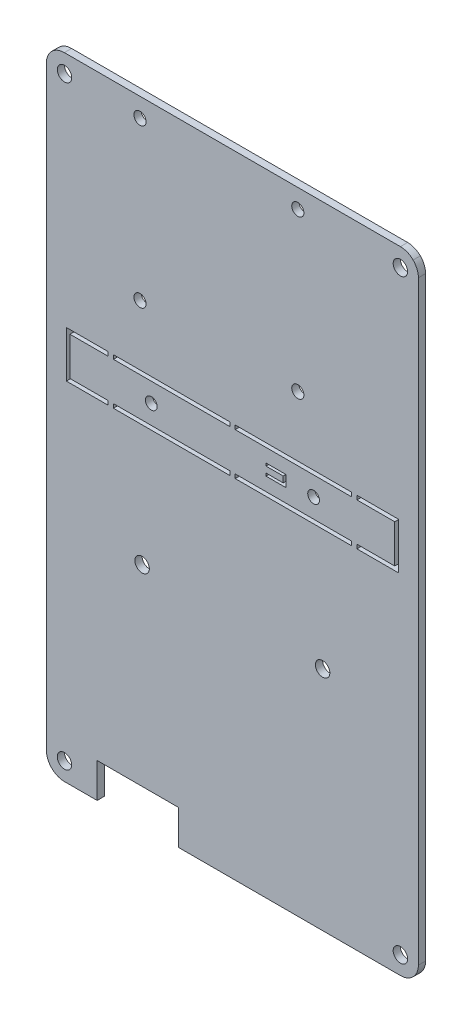
SolidWorks part; units mm, degrees
ref_plane "Front Plane" through (0, 0, 0) normal (0, 0, 1) x (1, 0, 0)
ref_plane "Top Plane" through (0, 0, 0) normal (0, 1, 0) x (1, 0, 0)
ref_plane "Right Plane" through (0, 0, 0) normal (1, 0, 0) x (0, 0, -1)
sketch "Model" plane through (0, 0, 0) normal (0, 0, 1) x (1, 0, 0)
  line L0 (70.0024, -162.3047) -> (88.0029, -162.3047)
  line L1 (72.4144, -82.5502) -> (63.1754, -82.5502)
  line L2 (72.4144, -83.4501) -> (63.9755, -83.4501)
  line L3 (72.4144, -91.9504) -> (72.4144, -92.8504)
  line L4 (73.6145, -82.5502) -> (73.6145, -83.4501)
  line L5 (126.4162, -82.5502) -> (126.4162, -83.4501)
  line L6 (73.6145, -91.9504) -> (73.6145, -92.8504)
  line L7 (126.4162, -91.9504) -> (126.4162, -92.8504)
  line L8 (127.6163, -91.9504) -> (127.6163, -92.8504)
  line L9 (127.6163, -82.5502) -> (127.6163, -83.4501)
  line L10 (136.0029, -91.9504) -> (136.0029, -83.4501)
  line L11 (136.8029, -82.5502) -> (136.8029, -92.8504)
  line L12 (73.6145, -83.4501) -> (99.4153, -83.4501)
  line L13 (88.0029, -162.3047) -> (88.0029, -169.9868)
  line L14 (141.2463, -33.9638) -> (141.2461, -165.9996)
  line L15 (107.4536, -86.4364) -> (111.8538, -86.4364)
  line L16 (107.4536, -88.3641) -> (111.2538, -88.3641)
  line L17 (70.0024, -169.9868) -> (62.7306, -169.9866)
  line L18 (100.6154, -82.5502) -> (100.6154, -83.4501)
  line L19 (100.6154, -91.9504) -> (100.6154, -92.8504)
  line L20 (100.6154, -91.9504) -> (126.4162, -91.9504)
  line L21 (99.4153, -91.9504) -> (99.4153, -92.8504)
  line L22 (63.1754, -82.5502) -> (63.1754, -92.8504)
  line L23 (72.4144, -82.5502) -> (72.4144, -83.4501)
  line L24 (73.6145, -92.8504) -> (99.4153, -92.8504)
  line L25 (111.8538, -86.4364) -> (111.8538, -88.9641)
  line L26 (107.4536, -88.3641) -> (107.4536, -88.9641)
  line L27 (106.1536, -88.9641) -> (106.7536, -88.9641) construction
  line L28 (107.4536, -87.0364) -> (111.2538, -87.0364)
  line L29 (106.7536, -86.4364) -> (106.7536, -88.9641) construction
  line L30 (107.4536, -86.4364) -> (107.4536, -87.0364)
  line L31 (63.9755, -83.4501) -> (63.9755, -91.9504)
  line L32 (127.6163, -83.4501) -> (136.0029, -83.4501)
  line L33 (127.6163, -82.5502) -> (136.8029, -82.5502)
  line L34 (63.9755, -91.9504) -> (72.4144, -91.9504)
  line L35 (70.0024, -169.9868) -> (70.0024, -162.3047)
  line L36 (106.1536, -86.4364) -> (106.1536, -88.9641) construction
  line L37 (100.6154, -82.5502) -> (126.4162, -82.5502)
  line L38 (137.2589, -29.9767) -> (62.7305, -29.9767)
  line L39 (88.0029, -169.9868) -> (137.2587, -169.9868)
  line L40 (127.6163, -91.9504) -> (136.0029, -91.9504)
  line L41 (111.2538, -87.0364) -> (111.2538, -88.3641)
  line L42 (107.4536, -88.9641) -> (111.8538, -88.9641)
  line L43 (73.6145, -82.5502) -> (99.4153, -82.5502)
  line L44 (106.1536, -86.4364) -> (106.7536, -86.4364) construction
  line L45 (73.6145, -91.9504) -> (99.4153, -91.9504)
  line L46 (100.6154, -83.4501) -> (126.4162, -83.4501)
  line L47 (63.1754, -92.8504) -> (72.4144, -92.8504)
  line L48 (127.6163, -92.8504) -> (136.8029, -92.8504)
  line L49 (100.6154, -92.8504) -> (126.4162, -92.8504)
  line L50 (99.4153, -82.5502) -> (99.4153, -83.4501)
  line L51 (58.7434, -33.964) -> (58.7432, -165.9996)
  line L52 (135.6894, -83.7631) -> (73.0025, -83.7631) construction
  line L53 (73.0025, -91.6374) -> (135.6894, -91.6374) construction
  line L54 (70.4607, -86.0492) -> (64.289, -86.0492) construction
  line L55 (70.7147, -86.0492) -> (135.6894, -86.0492) construction
  line L56 (64.289, -89.3513) -> (70.4607, -89.3513) construction
  line L57 (72.7467, -91.6374) -> (64.289, -91.6374) construction
  line L58 (135.6894, -89.3513) -> (70.7147, -89.3513) construction
  line L59 (64.289, -83.7631) -> (72.7467, -83.7631) construction
  line L60 (69.5023, -87.3002) -> (69.5023, -88.1003) construction
  line L61 (69.5023, -88.1003) -> (69.0023, -88.1003) construction
  line L62 (69.0023, -88.1003) -> (69.0023, -87.3002) construction
  line L63 (69.0023, -87.3002) -> (69.5023, -87.3002) construction
  line L64 (68.0023, -87.3002) -> (68.0023, -88.1003) construction
  line L65 (68.0023, -88.1003) -> (67.5023, -88.1003) construction
  line L66 (67.5023, -88.1003) -> (67.5023, -87.3002) construction
  line L67 (67.5023, -87.3002) -> (68.0023, -87.3002) construction
  line L68 (78.5026, -87.3002) -> (78.5026, -88.1003) construction
  line L69 (78.5026, -88.1003) -> (78.0026, -88.1003) construction
  line L70 (78.0026, -88.1003) -> (78.0026, -87.3002) construction
  line L71 (78.0026, -87.3002) -> (78.5026, -87.3002) construction
  line L72 (77.0026, -87.3002) -> (77.0026, -88.1003) construction
  line L73 (77.0026, -88.1003) -> (76.5026, -88.1003) construction
  line L74 (76.5026, -88.1003) -> (76.5026, -87.3002) construction
  line L75 (76.5026, -87.3002) -> (77.0026, -87.3002) construction
  line L76 (87.503, -87.3002) -> (87.503, -88.1003) construction
  line L77 (87.503, -88.1003) -> (87.0029, -88.1003) construction
  line L78 (87.0029, -88.1003) -> (87.0029, -87.3002) construction
  line L79 (87.0029, -87.3002) -> (87.503, -87.3002) construction
  line L80 (86.0029, -87.3002) -> (86.0029, -88.1003) construction
  line L81 (86.0029, -88.1003) -> (85.5029, -88.1003) construction
  line L82 (85.5029, -88.1003) -> (85.5029, -87.3002) construction
  line L83 (85.5029, -87.3002) -> (86.0029, -87.3002) construction
  line L84 (96.5033, -87.3002) -> (96.5033, -88.1003) construction
  line L85 (96.5033, -88.1003) -> (96.0032, -88.1003) construction
  line L86 (96.0032, -88.1003) -> (96.0032, -87.3002) construction
  line L87 (96.0032, -87.3002) -> (96.5033, -87.3002) construction
  line L88 (95.0032, -87.3002) -> (95.0032, -88.1003) construction
  line L89 (95.0032, -88.1003) -> (94.5032, -88.1003) construction
  line L90 (94.5032, -88.1003) -> (94.5032, -87.3002) construction
  line L91 (94.5032, -87.3002) -> (95.0032, -87.3002) construction
  line L92 (105.5036, -87.3002) -> (105.5036, -88.1003) construction
  line L93 (105.5036, -88.1003) -> (105.0035, -88.1003) construction
  line L94 (105.0035, -88.1003) -> (105.0035, -87.3002) construction
  line L95 (105.0035, -87.3002) -> (105.5036, -87.3002) construction
  line L96 (104.0035, -87.3002) -> (104.0035, -88.1003) construction
  line L97 (104.0035, -88.1003) -> (103.5035, -88.1003) construction
  line L98 (103.5035, -88.1003) -> (103.5035, -87.3002) construction
  line L99 (103.5035, -87.3002) -> (104.0035, -87.3002) construction
  line L100 (123.5042, -87.3002) -> (123.5042, -88.1003) construction
  line L101 (123.5042, -88.1003) -> (123.0042, -88.1003) construction
  line L102 (123.0042, -88.1003) -> (123.0042, -87.3002) construction
  line L103 (123.0042, -87.3002) -> (123.5042, -87.3002) construction
  line L104 (122.0041, -87.3002) -> (122.0041, -88.1003) construction
  line L105 (122.0041, -88.1003) -> (121.5041, -88.1003) construction
  line L106 (121.5041, -88.1003) -> (121.5041, -87.3002) construction
  line L107 (121.5041, -87.3002) -> (122.0041, -87.3002) construction
  line L108 (114.5039, -87.3002) -> (114.5039, -88.1003) construction
  line L109 (114.5039, -88.1003) -> (114.0038, -88.1003) construction
  line L110 (114.0038, -88.1003) -> (114.0038, -87.3002) construction
  line L111 (114.0038, -87.3002) -> (114.5039, -87.3002) construction
  line L112 (113.0038, -87.3002) -> (113.0038, -88.1003) construction
  line L113 (113.0038, -88.1003) -> (112.5038, -88.1003) construction
  line L114 (112.5038, -88.1003) -> (112.5038, -87.3002) construction
  line L115 (112.5038, -87.3002) -> (113.0038, -87.3002) construction
  line L116 (110.9637, -87.8702) -> (110.9531, -87.9238) construction
  line L117 (110.9531, -87.9238) -> (110.9227, -87.9692) construction
  line L118 (110.9227, -87.9692) -> (110.8773, -87.9996) construction
  line L119 (110.8773, -87.9996) -> (110.8237, -88.0102) construction
  line L120 (110.8237, -88.0102) -> (110.5437, -88.0102) construction
  line L121 (110.5437, -88.0102) -> (110.4901, -87.9996) construction
  line L122 (110.4901, -87.9996) -> (110.4447, -87.9692) construction
  line L123 (110.4447, -87.9692) -> (110.4144, -87.9238) construction
  line L124 (110.4144, -87.9238) -> (110.4037, -87.8702) construction
  line L125 (110.4037, -87.8702) -> (110.4037, -87.5302) construction
  line L126 (110.4037, -87.5302) -> (110.4144, -87.4767) construction
  line L127 (110.4144, -87.4767) -> (110.4447, -87.4312) construction
  line L128 (110.4447, -87.4312) -> (110.4901, -87.4009) construction
  line L129 (110.4901, -87.4009) -> (110.5437, -87.3902) construction
  line L130 (110.5437, -87.3902) -> (110.8237, -87.3902) construction
  line L131 (110.8237, -87.3902) -> (110.8773, -87.4009) construction
  line L132 (110.8773, -87.4009) -> (110.9227, -87.4312) construction
  line L133 (110.9227, -87.4312) -> (110.9531, -87.4767) construction
  line L134 (110.9531, -87.4767) -> (110.9637, -87.5302) construction
  line L135 (110.9637, -87.5302) -> (110.9637, -87.8702) construction
  line L136 (110.0037, -87.8702) -> (109.9931, -87.9238) construction
  line L137 (109.9931, -87.9238) -> (109.9627, -87.9692) construction
  line L138 (109.9627, -87.9692) -> (109.9173, -87.9996) construction
  line L139 (109.9173, -87.9996) -> (109.8637, -88.0102) construction
  line L140 (109.8637, -88.0102) -> (109.5837, -88.0102) construction
  line L141 (109.5837, -88.0102) -> (109.5301, -87.9996) construction
  line L142 (109.5301, -87.9996) -> (109.4847, -87.9692) construction
  line L143 (109.4847, -87.9692) -> (109.4544, -87.9238) construction
  line L144 (109.4544, -87.9238) -> (109.4437, -87.8702) construction
  line L145 (109.4437, -87.8702) -> (109.4437, -87.5302) construction
  line L146 (109.4437, -87.5302) -> (109.4544, -87.4767) construction
  line L147 (109.4544, -87.4767) -> (109.4847, -87.4312) construction
  line L148 (109.4847, -87.4312) -> (109.5301, -87.4009) construction
  line L149 (109.5301, -87.4009) -> (109.5837, -87.3902) construction
  line L150 (109.5837, -87.3902) -> (109.8637, -87.3902) construction
  line L151 (109.8637, -87.3902) -> (109.9173, -87.4009) construction
  line L152 (109.9173, -87.4009) -> (109.9627, -87.4312) construction
  line L153 (109.9627, -87.4312) -> (109.9931, -87.4767) construction
  line L154 (109.9931, -87.4767) -> (110.0037, -87.5302) construction
  line L155 (110.0037, -87.5302) -> (110.0037, -87.8702) construction
  line L156 (132.5045, -87.3002) -> (132.5045, -88.1003) construction
  line L157 (132.5045, -88.1003) -> (132.0045, -88.1003) construction
  line L158 (132.0045, -88.1003) -> (132.0045, -87.3002) construction
  line L159 (132.0045, -87.3002) -> (132.5045, -87.3002) construction
  line L160 (131.0044, -87.3002) -> (131.0044, -88.1003) construction
  line L161 (131.0044, -88.1003) -> (130.5044, -88.1003) construction
  line L162 (130.5044, -88.1003) -> (130.5044, -87.3002) construction
  line L163 (130.5044, -87.3002) -> (131.0044, -87.3002) construction
  line L164 (129.463, -38.0569) -> (129.4631, -31.1764) construction
  line L165 (121.4884, -38.057) -> (121.4884, -31.1764) construction
  line L166 (140.0614, -33.9896) -> (140.0614, -166.0159) construction
  line L167 (137.2606, -168.8164) -> (62.7465, -168.8164) construction
  line L168 (137.2606, -31.1891) -> (62.7465, -31.1891) construction
  line L169 (59.9457, -33.9896) -> (59.9457, -166.0159) construction
  line L170 (138.0026, -151.9543) -> (139.0027, -151.9543) construction
  line L171 (139.0027, -151.9543) -> (139.0027, -152.8544) construction
  line L172 (139.0027, -152.8544) -> (138.0026, -152.8544) construction
  line L173 (138.0026, -152.8544) -> (138.0026, -151.9543) construction
  line L174 (138.0026, -156.0545) -> (139.0027, -156.0545) construction
  line L175 (139.0027, -156.0545) -> (139.0027, -156.9545) construction
  line L176 (139.0027, -156.9545) -> (138.0026, -156.9545) construction
  line L177 (138.0026, -156.9545) -> (138.0026, -156.0545) construction
  line L178 (136.4026, -156.0545) -> (137.4026, -156.0545) construction
  line L179 (137.4026, -156.0545) -> (137.4026, -156.9545) construction
  line L180 (137.4026, -156.9545) -> (136.4026, -156.9545) construction
  line L181 (136.4026, -156.9545) -> (136.4026, -156.0545) construction
  line L182 (136.4026, -151.9543) -> (137.4026, -151.9543) construction
  line L183 (137.4026, -151.9543) -> (137.4026, -152.8544) construction
  line L184 (137.4026, -152.8544) -> (136.4026, -152.8544) construction
  line L185 (136.4026, -152.8544) -> (136.4026, -151.9543) construction
  line L186 (74.8825, -163.3947) -> (74.8825, -123.0934) construction
  line L187 (129.2444, -123.0934) -> (74.8825, -123.0934) construction
  line L188 (129.2444, -163.3947) -> (74.8825, -163.3947) construction
  line L189 (129.2444, -123.0934) -> (129.2444, -163.3947) construction
  line L190 (131.5044, -124.5034) -> (131.5044, -162.0047) construction
  line L191 (77.1826, -160.5046) -> (77.1826, -126.0035) construction
  line L192 (122.8241, -126.0035) -> (122.8241, -160.5046) construction
  line L193 (122.8241, -126.0035) -> (77.1826, -126.0035) construction
  line L194 (129.5044, -124.5034) -> (129.5044, -162.0047) construction
  line L195 (122.8241, -160.4846) -> (77.1826, -160.4846) construction
  line L196 (107.0536, -155.0434) -> (107.0536, -153.7434) construction
  line L197 (107.0536, -153.7434) -> (109.0537, -153.7434) construction
  line L198 (109.0537, -153.7434) -> (109.0537, -155.0434) construction
  line L199 (109.0537, -155.0434) -> (107.0536, -155.0434) construction
  line L200 (90.9531, -155.0434) -> (90.9531, -153.7434) construction
  line L201 (90.9531, -153.7434) -> (92.9531, -153.7434) construction
  line L202 (92.9531, -153.7434) -> (92.9531, -155.0434) construction
  line L203 (92.9531, -155.0434) -> (90.9531, -155.0434) construction
  line L204 (105.6036, -152.1933) -> (105.6036, -151.1933) construction
  line L205 (105.6036, -151.1933) -> (105.9036, -151.1933) construction
  line L206 (105.9036, -151.1933) -> (105.9036, -152.1933) construction
  line L207 (105.9036, -152.1933) -> (105.6036, -152.1933) construction
  line L208 (105.1035, -152.1933) -> (105.1035, -151.1933) construction
  line L209 (105.1035, -151.1933) -> (105.4036, -151.1933) construction
  line L210 (105.4036, -151.1933) -> (105.4036, -152.1933) construction
  line L211 (105.4036, -152.1933) -> (105.1035, -152.1933) construction
  line L212 (104.6035, -152.1933) -> (104.6035, -151.1933) construction
  line L213 (104.6035, -151.1933) -> (104.9035, -151.1933) construction
  line L214 (104.9035, -151.1933) -> (104.9035, -152.1933) construction
  line L215 (104.9035, -152.1933) -> (104.6035, -152.1933) construction
  line L216 (104.1035, -152.1933) -> (104.1035, -151.1933) construction
  line L217 (104.1035, -151.1933) -> (104.4035, -151.1933) construction
  line L218 (104.4035, -151.1933) -> (104.4035, -152.1933) construction
  line L219 (104.4035, -152.1933) -> (104.1035, -152.1933) construction
  line L220 (103.6035, -152.1933) -> (103.6035, -151.1933) construction
  line L221 (103.6035, -151.1933) -> (103.9035, -151.1933) construction
  line L222 (103.9035, -151.1933) -> (103.9035, -152.1933) construction
  line L223 (103.9035, -152.1933) -> (103.6035, -152.1933) construction
  line L224 (103.1035, -152.1933) -> (103.1035, -151.1933) construction
  line L225 (103.1035, -151.1933) -> (103.4035, -151.1933) construction
  line L226 (103.4035, -151.1933) -> (103.4035, -152.1933) construction
  line L227 (103.4035, -152.1933) -> (103.1035, -152.1933) construction
  line L228 (102.6035, -152.1933) -> (102.6035, -151.1933) construction
  line L229 (102.6035, -151.1933) -> (102.9035, -151.1933) construction
  line L230 (102.9035, -151.1933) -> (102.9035, -152.1933) construction
  line L231 (102.9035, -152.1933) -> (102.6035, -152.1933) construction
  line L232 (102.1034, -152.1933) -> (102.1034, -151.1933) construction
  line L233 (102.1034, -151.1933) -> (102.4035, -151.1933) construction
  line L234 (102.4035, -151.1933) -> (102.4035, -152.1933) construction
  line L235 (102.4035, -152.1933) -> (102.1034, -152.1933) construction
  line L236 (101.6034, -152.1933) -> (101.6034, -151.1933) construction
  line L237 (101.6034, -151.1933) -> (101.9034, -151.1933) construction
  line L238 (101.9034, -151.1933) -> (101.9034, -152.1933) construction
  line L239 (101.9034, -152.1933) -> (101.6034, -152.1933) construction
  line L240 (101.1034, -152.1933) -> (101.1034, -151.1933) construction
  line L241 (101.1034, -151.1933) -> (101.4034, -151.1933) construction
  line L242 (101.4034, -151.1933) -> (101.4034, -152.1933) construction
  line L243 (101.4034, -152.1933) -> (101.1034, -152.1933) construction
  line L244 (100.6034, -152.1933) -> (100.6034, -151.1933) construction
  line L245 (100.6034, -151.1933) -> (100.9034, -151.1933) construction
  line L246 (100.9034, -151.1933) -> (100.9034, -152.1933) construction
  line L247 (100.9034, -152.1933) -> (100.6034, -152.1933) construction
  line L248 (100.1034, -152.1933) -> (100.1034, -151.1933) construction
  line L249 (100.1034, -151.1933) -> (100.4034, -151.1933) construction
  line L250 (100.4034, -151.1933) -> (100.4034, -152.1933) construction
  line L251 (100.4034, -152.1933) -> (100.1034, -152.1933) construction
  line L252 (99.6034, -152.1933) -> (99.6034, -151.1933) construction
  line L253 (99.6034, -151.1933) -> (99.9034, -151.1933) construction
  line L254 (99.9034, -151.1933) -> (99.9034, -152.1933) construction
  line L255 (99.9034, -152.1933) -> (99.6034, -152.1933) construction
  line L256 (99.1033, -152.1933) -> (99.1033, -151.1933) construction
  line L257 (99.1033, -151.1933) -> (99.4034, -151.1933) construction
  line L258 (99.4034, -151.1933) -> (99.4034, -152.1933) construction
  line L259 (99.4034, -152.1933) -> (99.1033, -152.1933) construction
  line L260 (98.6033, -152.1933) -> (98.6033, -151.1933) construction
  line L261 (98.6033, -151.1933) -> (98.9033, -151.1933) construction
  line L262 (98.9033, -151.1933) -> (98.9033, -152.1933) construction
  line L263 (98.9033, -152.1933) -> (98.6033, -152.1933) construction
  line L264 (98.1033, -152.1933) -> (98.1033, -151.1933) construction
  line L265 (98.1033, -151.1933) -> (98.4033, -151.1933) construction
  line L266 (98.4033, -151.1933) -> (98.4033, -152.1933) construction
  line L267 (98.4033, -152.1933) -> (98.1033, -152.1933) construction
  line L268 (97.6033, -152.1933) -> (97.6033, -151.1933) construction
  line L269 (97.6033, -151.1933) -> (97.9033, -151.1933) construction
  line L270 (97.9033, -151.1933) -> (97.9033, -152.1933) construction
  line L271 (97.9033, -152.1933) -> (97.6033, -152.1933) construction
  line L272 (97.1033, -152.1933) -> (97.1033, -151.1933) construction
  line L273 (97.1033, -151.1933) -> (97.4033, -151.1933) construction
  line L274 (97.4033, -151.1933) -> (97.4033, -152.1933) construction
  line L275 (97.4033, -152.1933) -> (97.1033, -152.1933) construction
  line L276 (96.6033, -152.1933) -> (96.6033, -151.1933) construction
  line L277 (96.6033, -151.1933) -> (96.9033, -151.1933) construction
  line L278 (96.9033, -151.1933) -> (96.9033, -152.1933) construction
  line L279 (96.9033, -152.1933) -> (96.6033, -152.1933) construction
  line L280 (96.1032, -152.1933) -> (96.1032, -151.1933) construction
  line L281 (96.1032, -151.1933) -> (96.4033, -151.1933) construction
  line L282 (96.4033, -151.1933) -> (96.4033, -152.1933) construction
  line L283 (96.4033, -152.1933) -> (96.1032, -152.1933) construction
  line L284 (95.6032, -152.1933) -> (95.6032, -151.1933) construction
  line L285 (95.6032, -151.1933) -> (95.9032, -151.1933) construction
  line L286 (95.9032, -151.1933) -> (95.9032, -152.1933) construction
  line L287 (95.9032, -152.1933) -> (95.6032, -152.1933) construction
  line L288 (95.1032, -152.1933) -> (95.1032, -151.1933) construction
  line L289 (95.1032, -151.1933) -> (95.4032, -151.1933) construction
  line L290 (95.4032, -151.1933) -> (95.4032, -152.1933) construction
  line L291 (95.4032, -152.1933) -> (95.1032, -152.1933) construction
  line L292 (94.6032, -152.1933) -> (94.6032, -151.1933) construction
  line L293 (94.6032, -151.1933) -> (94.9032, -151.1933) construction
  line L294 (94.9032, -151.1933) -> (94.9032, -152.1933) construction
  line L295 (94.9032, -152.1933) -> (94.6032, -152.1933) construction
  line L296 (94.1032, -152.1933) -> (94.1032, -151.1933) construction
  line L297 (94.1032, -151.1933) -> (94.4032, -151.1933) construction
  line L298 (94.4032, -151.1933) -> (94.4032, -152.1933) construction
  line L299 (94.4032, -152.1933) -> (94.1032, -152.1933) construction
  line L300 (137.0864, -46.2988) -> (137.0027, -46.2821) construction
  line L301 (137.0027, -46.2821) -> (136.9317, -46.2347) construction
  line L302 (136.9317, -46.2347) -> (136.8843, -46.1637) construction
  line L303 (136.8843, -46.1637) -> (136.8676, -46.08) construction
  line L304 (136.8676, -46.08) -> (136.8676, -45.6425) construction
  line L305 (136.8676, -45.6425) -> (136.8843, -45.5588) construction
  line L306 (136.8843, -45.5588) -> (136.9317, -45.4878) construction
  line L307 (136.9317, -45.4878) -> (137.0027, -45.4404) construction
  line L308 (137.0027, -45.4404) -> (137.0864, -45.4237) construction
  line L309 (137.0864, -45.4237) -> (137.5989, -45.4237) construction
  line L310 (137.5989, -45.4237) -> (137.6826, -45.4404) construction
  line L311 (137.6826, -45.4404) -> (137.7536, -45.4878) construction
  line L312 (137.7536, -45.4878) -> (137.801, -45.5588) construction
  line L313 (137.801, -45.5588) -> (137.8177, -45.6425) construction
  line L314 (137.8177, -45.6425) -> (137.8177, -46.08) construction
  line L315 (137.8177, -46.08) -> (137.801, -46.1637) construction
  line L316 (137.801, -46.1637) -> (137.7536, -46.2347) construction
  line L317 (137.7536, -46.2347) -> (137.6826, -46.2821) construction
  line L318 (137.6826, -46.2821) -> (137.5989, -46.2988) construction
  line L319 (137.5989, -46.2988) -> (137.0864, -46.2988) construction
  line L320 (137.0864, -44.7237) -> (137.0027, -44.7071) construction
  line L321 (137.0027, -44.7071) -> (136.9317, -44.6596) construction
  line L322 (136.9317, -44.6596) -> (136.8843, -44.5887) construction
  line L323 (136.8843, -44.5887) -> (136.8676, -44.505) construction
  line L324 (136.8676, -44.505) -> (136.8676, -44.0674) construction
  line L325 (136.8676, -44.0674) -> (136.8843, -43.9837) construction
  line L326 (136.8843, -43.9837) -> (136.9317, -43.9128) construction
  line L327 (136.9317, -43.9128) -> (137.0027, -43.8653) construction
  line L328 (137.0027, -43.8653) -> (137.0864, -43.8487) construction
  line L329 (137.0864, -43.8487) -> (137.5989, -43.8487) construction
  line L330 (137.5989, -43.8487) -> (137.6826, -43.8653) construction
  line L331 (137.6826, -43.8653) -> (137.7536, -43.9128) construction
  line L332 (137.7536, -43.9128) -> (137.801, -43.9837) construction
  line L333 (137.801, -43.9837) -> (137.8177, -44.0674) construction
  line L334 (137.8177, -44.0674) -> (137.8177, -44.505) construction
  line L335 (137.8177, -44.505) -> (137.801, -44.5887) construction
  line L336 (137.801, -44.5887) -> (137.7536, -44.6596) construction
  line L337 (137.7536, -44.6596) -> (137.6826, -44.7071) construction
  line L338 (137.6826, -44.7071) -> (137.5989, -44.7237) construction
  line L339 (137.5989, -44.7237) -> (137.0864, -44.7237) construction
  line L340 (127.8663, -61.6353) -> (124.4662, -61.6353) construction
  line L341 (124.4662, -61.6353) -> (124.4662, -60.1352) construction
  line L342 (124.4662, -60.1352) -> (127.8663, -60.1352) construction
  line L343 (127.8663, -60.1352) -> (127.8663, -61.6353) construction
  line L344 (127.8663, -68.3355) -> (124.4662, -68.3355) construction
  line L345 (124.4662, -68.3355) -> (124.4662, -66.8355) construction
  line L346 (124.4662, -66.8355) -> (127.8663, -66.8355) construction
  line L347 (127.8663, -66.8355) -> (127.8663, -68.3355) construction
  line L348 (122.3661, -65.7354) -> (118.866, -65.7354) construction
  line L349 (118.866, -65.7354) -> (118.866, -64.7354) construction
  line L350 (118.866, -64.7354) -> (122.3661, -64.7354) construction
  line L351 (122.3661, -64.7354) -> (122.3661, -65.7354) construction
  line L352 (122.3661, -63.7354) -> (118.866, -63.7354) construction
  line L353 (118.866, -63.7354) -> (118.866, -62.7353) construction
  line L354 (118.866, -62.7353) -> (122.3661, -62.7353) construction
  line L355 (122.3661, -62.7353) -> (122.3661, -63.7354) construction
  line L356 (106.5049, -141.111) -> (103.5042, -141.111) construction
  line L357 (103.5042, -141.111) -> (96.503, -141.111) construction
  line L358 (138.3113, -94.4016) -> (134.4739, -94.4016) construction
  line L359 (93.5022, -141.111) -> (93.5022, -134.3455) construction
  line L360 (95.5025, -139.1104) -> (96.5026, -139.1104) construction
  line L361 (61.6958, -93.2013) -> (66.158, -93.2013) construction
  line L362 (66.158, -93.2013) -> (95.5025, -135.1096) construction
  line L363 (103.5042, -139.1104) -> (96.5026, -139.1104) construction
  line L364 (106.5049, -134.3455) -> (106.5049, -141.111) construction
  line L365 (103.5042, -139.1104) -> (104.5043, -139.1104) construction
  line L366 (104.5043, -135.1096) -> (133.8491, -93.2013) construction
  line L367 (80.461, -115.7206) -> (65.5332, -94.4016) construction
  line L368 (133.8491, -93.2013) -> (138.311, -93.2013) construction
  line L369 (95.5025, -135.1096) -> (95.5025, -139.1104) construction
  line L370 (134.4739, -94.4016) -> (119.5463, -115.7204) construction
  line L371 (104.5043, -139.1104) -> (104.5043, -135.1096) construction
  line L372 (65.5038, -94.3713) -> (61.6929, -94.3715) construction
  line L373 (96.503, -141.111) -> (93.5022, -141.111) construction
  line L374 (99.9947, -29.9767) -> (99.9947, -73.0923) construction
  line L375 (110.0037, -87.7002) -> (110.4037, -87.7002) construction
  line L376 (110.2037, -87.7002) -> (110.2037, -87.3002) construction
  circle A0 centre (118.004, -87.7002) radius 1.3
  circle A1 centre (82.0028, -87.7002) radius 1.3
  circle A2 centre (114.5039, -69.1936) radius 1.35
  circle A3 centre (79.5027, -69.1936) radius 1.35
  circle A4 centre (79.5027, -34.1925) radius 1.35
  circle A5 centre (114.5039, -34.1925) radius 1.35
  circle A6 centre (62.7521, -34.0004) radius 1.6
  circle A7 centre (137.2546, -34.0004) radius 1.6
  circle A8 centre (137.2546, -166.0048) radius 1.6
  circle A9 centre (62.7521, -166.0048) radius 1.6
  circle A10 centre (79.9704, -119.7065) radius 1.6
  circle A11 centre (120.0076, -119.7065) radius 1.6
  circle A12 centre (77.5027, -87.7002) radius 1.35 construction
  spline S0 degree 3 poles (62.7521, -32.4003) (62.105, -32.4003) (61.5215, -32.7901) (61.2739, -33.388) knots 0 0 0 0 1 1 1 1 construction
  spline S1 degree 3 poles (61.2739, -33.388) (61.0262, -33.9859) (61.1631, -34.6742) (61.6207, -35.1318) knots 0 0 0 0 1 1 1 1 construction
  spline S2 degree 3 poles (61.6207, -35.1318) (62.0783, -35.5894) (62.7665, -35.7263) (63.3644, -35.4786) knots 0 0 0 0 1 1 1 1 construction
  spline S3 degree 3 poles (63.3644, -35.4786) (63.9623, -35.231) (64.3522, -34.6475) (64.3522, -34.0004) knots 0 0 0 0 1 1 1 1 construction
  spline S4 degree 3 poles (64.3522, -34.0004) (64.3522, -33.576) (64.1836, -33.169) (63.8835, -32.8689) knots 0 0 0 0 1 1 1 1 construction
  spline S5 degree 3 poles (63.8835, -32.8689) (63.5835, -32.5689) (63.1765, -32.4003) (62.7521, -32.4003) knots 0 0 0 0 1 1 1 1 construction
  spline S6 degree 3 poles (137.2546, -32.4003) (136.6075, -32.4003) (136.024, -32.7901) (135.7764, -33.388) knots 0 0 0 0 1 1 1 1 construction
  spline S7 degree 3 poles (135.7764, -33.388) (135.5287, -33.9859) (135.6656, -34.6742) (136.1232, -35.1318) knots 0 0 0 0 1 1 1 1 construction
  spline S8 degree 3 poles (136.1232, -35.1318) (136.5808, -35.5894) (137.269, -35.7263) (137.8669, -35.4786) knots 0 0 0 0 1 1 1 1 construction
  spline S9 degree 3 poles (137.8669, -35.4786) (138.4648, -35.231) (138.8547, -34.6475) (138.8547, -34.0004) knots 0 0 0 0 1 1 1 1 construction
  spline S10 degree 3 poles (138.8547, -34.0004) (138.8547, -33.576) (138.6861, -33.169) (138.386, -32.8689) knots 0 0 0 0 1 1 1 1 construction
  spline S11 degree 3 poles (138.386, -32.8689) (138.086, -32.5689) (137.679, -32.4003) (137.2546, -32.4003) knots 0 0 0 0 1 1 1 1 construction
  spline S12 degree 3 poles (62.7521, -164.4048) (62.105, -164.4048) (61.5215, -164.7946) (61.2739, -165.3925) knots 0 0 0 0 1 1 1 1 construction
  spline S13 degree 3 poles (61.2739, -165.3925) (61.0262, -165.9904) (61.1631, -166.6786) (61.6207, -167.1362) knots 0 0 0 0 1 1 1 1 construction
  spline S14 degree 3 poles (61.6207, -167.1362) (62.0783, -167.5938) (62.7665, -167.7307) (63.3644, -167.4831) knots 0 0 0 0 1 1 1 1 construction
  spline S15 degree 3 poles (63.3644, -167.4831) (63.9623, -167.2354) (64.3522, -166.652) (64.3522, -166.0048) knots 0 0 0 0 1 1 1 1 construction
  spline S16 degree 3 poles (64.3522, -166.0048) (64.3522, -165.5805) (64.1836, -165.1735) (63.8835, -164.8734) knots 0 0 0 0 1 1 1 1 construction
  spline S17 degree 3 poles (63.8835, -164.8734) (63.5835, -164.5733) (63.1765, -164.4048) (62.7521, -164.4048) knots 0 0 0 0 1 1 1 1 construction
  spline S18 degree 3 poles (137.2546, -164.4048) (136.6075, -164.4048) (136.024, -164.7946) (135.7764, -165.3925) knots 0 0 0 0 1 1 1 1 construction
  spline S19 degree 3 poles (135.7764, -165.3925) (135.5287, -165.9904) (135.6656, -166.6786) (136.1232, -167.1362) knots 0 0 0 0 1 1 1 1 construction
  spline S20 degree 3 poles (136.1232, -167.1362) (136.5808, -167.5938) (137.269, -167.7307) (137.8669, -167.4831) knots 0 0 0 0 1 1 1 1 construction
  spline S21 degree 3 poles (137.8669, -167.4831) (138.4648, -167.2354) (138.8547, -166.652) (138.8547, -166.0048) knots 0 0 0 0 1 1 1 1 construction
  spline S22 degree 3 poles (138.8547, -166.0048) (138.8547, -165.5805) (138.6861, -165.1735) (138.386, -164.8734) knots 0 0 0 0 1 1 1 1 construction
  spline S23 degree 3 poles (138.386, -164.8734) (138.086, -164.5733) (137.679, -164.4048) (137.2546, -164.4048) knots 0 0 0 0 1 1 1 1 construction
  spline S24 degree 3 poles (79.9704, -118.1065) (79.3232, -118.1065) (78.7398, -118.4964) (78.4921, -119.0943) knots 0 0 0 0 1 1 1 1 construction
  spline S25 degree 3 poles (78.4921, -119.0943) (78.2445, -119.6922) (78.3813, -120.3804) (78.839, -120.838) knots 0 0 0 0 1 1 1 1 construction
  spline S26 degree 3 poles (78.839, -120.838) (79.2966, -121.2956) (79.9848, -121.4325) (80.5827, -121.1849) knots 0 0 0 0 1 1 1 1 construction
  spline S27 degree 3 poles (80.5827, -121.1849) (81.1806, -120.9372) (81.5704, -120.3538) (81.5704, -119.7066) knots 0 0 0 0 1 1 1 1 construction
  spline S28 degree 3 poles (81.5704, -119.7066) (81.5704, -118.8229) (80.8541, -118.1065) (79.9704, -118.1065) knots 0 0 0 0 1 1 1 1 construction
  spline S29 degree 3 poles (120.0076, -118.1065) (119.3605, -118.1065) (118.777, -118.4964) (118.5294, -119.0943) knots 0 0 0 0 1 1 1 1 construction
  spline S30 degree 3 poles (118.5294, -119.0943) (118.2817, -119.6922) (118.4186, -120.3804) (118.8762, -120.838) knots 0 0 0 0 1 1 1 1 construction
  spline S31 degree 3 poles (118.8762, -120.838) (119.3338, -121.2956) (120.022, -121.4325) (120.6199, -121.1849) knots 0 0 0 0 1 1 1 1 construction
  spline S32 degree 3 poles (120.6199, -121.1849) (121.2178, -120.9372) (121.6077, -120.3538) (121.6077, -119.7066) knots 0 0 0 0 1 1 1 1 construction
  spline S33 degree 3 poles (121.6077, -119.7066) (121.6077, -119.2822) (121.4391, -118.8753) (121.139, -118.5752) knots 0 0 0 0 1 1 1 1 construction
  spline S34 degree 3 poles (121.139, -118.5752) (120.839, -118.2751) (120.432, -118.1065) (120.0076, -118.1065) knots 0 0 0 0 1 1 1 1 construction
  spline S35 degree 3 poles (118.004, -86.4002) (117.4782, -86.4002) (117.0041, -86.7169) (116.8029, -87.2027) knots 0 0 0 0 1 1 1 1 construction
  spline S36 degree 3 poles (116.8029, -87.2027) (116.6017, -87.6885) (116.7129, -88.2477) (117.0847, -88.6195) knots 0 0 0 0 1 1 1 1 construction
  spline S37 degree 3 poles (117.0847, -88.6195) (117.4565, -88.9913) (118.0157, -89.1025) (118.5015, -88.9013) knots 0 0 0 0 1 1 1 1 construction
  spline S38 degree 3 poles (118.5015, -88.9013) (118.9873, -88.7001) (119.304, -88.2261) (119.304, -87.7002) knots 0 0 0 0 1 1 1 1 construction
  spline S39 degree 3 poles (119.304, -87.7002) (119.304, -87.3554) (119.1671, -87.0248) (118.9233, -86.781) knots 0 0 0 0 1 1 1 1 construction
  spline S40 degree 3 poles (118.9233, -86.781) (118.6794, -86.5372) (118.3488, -86.4002) (118.004, -86.4002) knots 0 0 0 0 1 1 1 1 construction
  spline S41 degree 3 poles (82.0028, -86.4002) (81.4769, -86.4002) (81.0029, -86.7169) (80.8017, -87.2027) knots 0 0 0 0 1 1 1 1 construction
  spline S42 degree 3 poles (80.8017, -87.2027) (80.6005, -87.6885) (80.7117, -88.2477) (81.0835, -88.6195) knots 0 0 0 0 1 1 1 1 construction
  spline S43 degree 3 poles (81.0835, -88.6195) (81.4553, -88.9913) (82.0145, -89.1025) (82.5003, -88.9013) knots 0 0 0 0 1 1 1 1 construction
  spline S44 degree 3 poles (82.5003, -88.9013) (82.9861, -88.7001) (83.3028, -88.2261) (83.3028, -87.7002) knots 0 0 0 0 1 1 1 1 construction
  spline S45 degree 3 poles (83.3028, -87.7002) (83.3028, -86.9822) (82.7208, -86.4002) (82.0028, -86.4002) knots 0 0 0 0 1 1 1 1 construction
  spline S46 degree 3 poles (58.7432, -165.9996) (58.7432, -168.2018) (60.5284, -169.9869) (62.7306, -169.9866) knots 0 0 0 0 1 1 1 1
  spline S47 degree 3 poles (62.7305, -29.9767) (61.673, -29.9767) (60.6589, -30.3968) (59.9111, -31.1446) knots 0 0 0 0 1 1 1 1
  spline S48 degree 3 poles (59.9111, -31.1446) (59.1634, -31.8923) (58.7434, -32.9065) (58.7434, -33.964) knots 0 0 0 0 1 1 1 1
  spline S49 degree 3 poles (141.2463, -33.9638) (141.2462, -32.9062) (140.8261, -31.892) (140.0784, -31.1443) knots 0 0 0 0 1 1 1 1
  spline S50 degree 3 poles (140.0784, -31.1443) (139.3306, -30.3965) (138.3164, -29.9764) (137.2589, -29.9767) knots 0 0 0 0 1 1 1 1
  spline S51 degree 3 poles (137.2587, -169.9868) (138.3162, -169.9868) (139.3303, -169.5667) (140.0781, -168.819) knots 0 0 0 0 1 1 1 1
  spline S52 degree 3 poles (140.0781, -168.819) (140.8258, -168.0712) (141.2459, -167.0571) (141.2461, -165.9996) knots 0 0 0 0 1 1 1 1
  spline S53 degree 3 poles (95.5032, -86.3502) (94.9572, -86.3502) (94.4649, -86.6791) (94.2559, -87.1836) knots 0 0 0 0 1 1 1 1 construction
  spline S54 degree 3 poles (94.2559, -87.1836) (94.047, -87.6881) (94.1625, -88.2687) (94.5486, -88.6549) knots 0 0 0 0 1 1 1 1 construction
  spline S55 degree 3 poles (94.5486, -88.6549) (94.9347, -89.041) (95.5154, -89.1565) (96.0199, -88.9475) knots 0 0 0 0 1 1 1 1 construction
  spline S56 degree 3 poles (96.0199, -88.9475) (96.5243, -88.7385) (96.8533, -88.2463) (96.8533, -87.7002) knots 0 0 0 0 1 1 1 1 construction
  spline S57 degree 3 poles (96.8533, -87.7002) (96.8533, -87.3422) (96.711, -86.9988) (96.4578, -86.7456) knots 0 0 0 0 1 1 1 1 construction
  spline S58 degree 3 poles (96.4578, -86.7456) (96.2047, -86.4924) (95.8613, -86.3502) (95.5032, -86.3502) knots 0 0 0 0 1 1 1 1 construction
  spline S59 degree 3 poles (104.5035, -86.3502) (103.9575, -86.3502) (103.4652, -86.6791) (103.2562, -87.1836) knots 0 0 0 0 1 1 1 1 construction
  spline S60 degree 3 poles (103.2562, -87.1836) (103.0473, -87.6881) (103.1628, -88.2687) (103.5489, -88.6549) knots 0 0 0 0 1 1 1 1 construction
  spline S61 degree 3 poles (103.5489, -88.6549) (103.935, -89.041) (104.5157, -89.1565) (105.0202, -88.9475) knots 0 0 0 0 1 1 1 1 construction
  spline S62 degree 3 poles (105.0202, -88.9475) (105.5246, -88.7385) (105.8536, -88.2463) (105.8536, -87.7002) knots 0 0 0 0 1 1 1 1 construction
  spline S63 degree 3 poles (105.8536, -87.7002) (105.8536, -87.3422) (105.7113, -86.9988) (105.4582, -86.7456) knots 0 0 0 0 1 1 1 1 construction
  spline S64 degree 3 poles (105.4582, -86.7456) (105.205, -86.4924) (104.8616, -86.3502) (104.5035, -86.3502) knots 0 0 0 0 1 1 1 1 construction
  spline S65 degree 3 poles (68.5023, -86.3502) (67.9563, -86.3502) (67.464, -86.6791) (67.255, -87.1836) knots 0 0 0 0 1 1 1 1 construction
  spline S66 degree 3 poles (67.255, -87.1836) (67.0461, -87.6881) (67.1616, -88.2687) (67.5477, -88.6549) knots 0 0 0 0 1 1 1 1 construction
  spline S67 degree 3 poles (67.5477, -88.6549) (67.9338, -89.041) (68.5145, -89.1565) (69.019, -88.9475) knots 0 0 0 0 1 1 1 1 construction
  spline S68 degree 3 poles (69.019, -88.9475) (69.5234, -88.7385) (69.8524, -88.2463) (69.8524, -87.7002) knots 0 0 0 0 1 1 1 1 construction
  spline S69 degree 3 poles (69.8524, -87.7002) (69.8524, -87.3422) (69.7101, -86.9988) (69.4569, -86.7456) knots 0 0 0 0 1 1 1 1 construction
  spline S70 degree 3 poles (69.4569, -86.7456) (69.2038, -86.4924) (68.8604, -86.3502) (68.5023, -86.3502) knots 0 0 0 0 1 1 1 1 construction
  spline S71 degree 3 poles (86.5029, -86.3502) (85.9569, -86.3502) (85.4646, -86.6791) (85.2556, -87.1836) knots 0 0 0 0 1 1 1 1 construction
  spline S72 degree 3 poles (85.2556, -87.1836) (85.0467, -87.6881) (85.1622, -88.2687) (85.5483, -88.6549) knots 0 0 0 0 1 1 1 1 construction
  spline S73 degree 3 poles (85.5483, -88.6549) (85.9344, -89.041) (86.5151, -89.1565) (87.0196, -88.9475) knots 0 0 0 0 1 1 1 1 construction
  spline S74 degree 3 poles (87.0196, -88.9475) (87.524, -88.7385) (87.853, -88.2463) (87.853, -87.7002) knots 0 0 0 0 1 1 1 1 construction
  spline S75 degree 3 poles (87.853, -87.7002) (87.853, -87.3422) (87.7107, -86.9988) (87.4575, -86.7456) knots 0 0 0 0 1 1 1 1 construction
  spline S76 degree 3 poles (87.4575, -86.7456) (87.2044, -86.4924) (86.861, -86.3502) (86.5029, -86.3502) knots 0 0 0 0 1 1 1 1 construction
  spline S77 degree 3 poles (122.5041, -86.3502) (121.9581, -86.3502) (121.4658, -86.6791) (121.2569, -87.1836) knots 0 0 0 0 1 1 1 1 construction
  spline S78 degree 3 poles (121.2569, -87.1836) (121.0479, -87.6881) (121.1634, -88.2687) (121.5495, -88.6549) knots 0 0 0 0 1 1 1 1 construction
  spline S79 degree 3 poles (121.5495, -88.6549) (121.9356, -89.041) (122.5163, -89.1565) (123.0208, -88.9475) knots 0 0 0 0 1 1 1 1 construction
  spline S80 degree 3 poles (123.0208, -88.9475) (123.5253, -88.7385) (123.8542, -88.2463) (123.8542, -87.7002) knots 0 0 0 0 1 1 1 1 construction
  spline S81 degree 3 poles (123.8542, -87.7002) (123.8542, -87.3422) (123.7119, -86.9988) (123.4588, -86.7456) knots 0 0 0 0 1 1 1 1 construction
  spline S82 degree 3 poles (123.4588, -86.7456) (123.2056, -86.4924) (122.8622, -86.3502) (122.5041, -86.3502) knots 0 0 0 0 1 1 1 1 construction
  spline S83 degree 3 poles (77.5026, -86.3502) (76.9566, -86.3502) (76.4643, -86.6791) (76.2553, -87.1836) knots 0 0 0 0 1 1 1 1 construction
  spline S84 degree 3 poles (76.2553, -87.1836) (76.0464, -87.6881) (76.1619, -88.2687) (76.548, -88.6549) knots 0 0 0 0 1 1 1 1 construction
  spline S85 degree 3 poles (76.548, -88.6549) (76.9341, -89.041) (77.5148, -89.1565) (78.0193, -88.9475) knots 0 0 0 0 1 1 1 1 construction
  spline S86 degree 3 poles (78.0193, -88.9475) (78.5237, -88.7385) (78.8527, -88.2463) (78.8527, -87.7002) knots 0 0 0 0 1 1 1 1 construction
  spline S87 degree 3 poles (78.8527, -87.7002) (78.8527, -87.3422) (78.7104, -86.9988) (78.4572, -86.7456) knots 0 0 0 0 1 1 1 1 construction
  spline S88 degree 3 poles (78.4572, -86.7456) (78.2041, -86.4924) (77.8607, -86.3502) (77.5026, -86.3502) knots 0 0 0 0 1 1 1 1 construction
  spline S89 degree 3 poles (113.5038, -86.3502) (112.9578, -86.3502) (112.4655, -86.6791) (112.2566, -87.1836) knots 0 0 0 0 1 1 1 1 construction
  spline S90 degree 3 poles (112.2566, -87.1836) (112.0476, -87.6881) (112.1631, -88.2687) (112.5492, -88.6549) knots 0 0 0 0 1 1 1 1 construction
  spline S91 degree 3 poles (112.5492, -88.6549) (112.9353, -89.041) (113.516, -89.1565) (114.0205, -88.9475) knots 0 0 0 0 1 1 1 1 construction
  spline S92 degree 3 poles (114.0205, -88.9475) (114.5249, -88.7385) (114.8539, -88.2463) (114.8539, -87.7002) knots 0 0 0 0 1 1 1 1 construction
  spline S93 degree 3 poles (114.8539, -87.7002) (114.8539, -87.3422) (114.7116, -86.9988) (114.4585, -86.7456) knots 0 0 0 0 1 1 1 1 construction
  spline S94 degree 3 poles (114.4585, -86.7456) (114.2053, -86.4924) (113.8619, -86.3502) (113.5038, -86.3502) knots 0 0 0 0 1 1 1 1 construction
  spline S95 degree 3 poles (131.5044, -86.3502) (130.9584, -86.3502) (130.4661, -86.6791) (130.2572, -87.1836) knots 0 0 0 0 1 1 1 1 construction
  spline S96 degree 3 poles (130.2572, -87.1836) (130.0482, -87.6881) (130.1637, -88.2687) (130.5498, -88.6549) knots 0 0 0 0 1 1 1 1 construction
  spline S97 degree 3 poles (130.5498, -88.6549) (130.9359, -89.041) (131.5166, -89.1565) (132.0211, -88.9475) knots 0 0 0 0 1 1 1 1 construction
  spline S98 degree 3 poles (132.0211, -88.9475) (132.5256, -88.7385) (132.8545, -88.2463) (132.8545, -87.7002) knots 0 0 0 0 1 1 1 1 construction
  spline S99 degree 3 poles (132.8545, -87.7002) (132.8545, -87.3422) (132.7122, -86.9988) (132.4591, -86.7456) knots 0 0 0 0 1 1 1 1 construction
  spline S100 degree 3 poles (132.4591, -86.7456) (132.2059, -86.4924) (131.8625, -86.3502) (131.5044, -86.3502) knots 0 0 0 0 1 1 1 1 construction
  spline S101 degree 3 poles (117.9904, -86.1414) (117.3663, -86.1414) (116.8037, -86.5173) (116.5649, -87.0938) knots 0 0 0 0 1 1 1 1 construction
  spline S102 degree 3 poles (116.5649, -87.0938) (116.3261, -87.6704) (116.4581, -88.334) (116.8994, -88.7753) knots 0 0 0 0 1 1 1 1 construction
  spline S103 degree 3 poles (116.8994, -88.7753) (117.3406, -89.2166) (118.0043, -89.3486) (118.5808, -89.1097) knots 0 0 0 0 1 1 1 1 construction
  spline S104 degree 3 poles (118.5808, -89.1097) (119.1574, -88.8709) (119.5333, -88.3083) (119.5333, -87.6843) knots 0 0 0 0 1 1 1 1 construction
  spline S105 degree 3 poles (119.5333, -87.6843) (119.5333, -87.2751) (119.3707, -86.8826) (119.0814, -86.5933) knots 0 0 0 0 1 1 1 1 construction
  spline S106 degree 3 poles (119.0814, -86.5933) (118.792, -86.3039) (118.3996, -86.1414) (117.9904, -86.1414) knots 0 0 0 0 1 1 1 1 construction
  spline S107 degree 3 poles (81.9819, -86.1413) (81.3578, -86.1413) (80.7952, -86.5173) (80.5564, -87.0938) knots 0 0 0 0 1 1 1 1 construction
  spline S108 degree 3 poles (80.5564, -87.0938) (80.3176, -87.6703) (80.4496, -88.334) (80.8909, -88.7752) knots 0 0 0 0 1 1 1 1 construction
  spline S109 degree 3 poles (80.8909, -88.7752) (81.3321, -89.2165) (81.9958, -89.3485) (82.5723, -89.1097) knots 0 0 0 0 1 1 1 1 construction
  spline S110 degree 3 poles (82.5723, -89.1097) (83.1489, -88.8709) (83.5248, -88.3083) (83.5248, -87.6842) knots 0 0 0 0 1 1 1 1 construction
  spline S111 degree 3 poles (83.5248, -87.6842) (83.5248, -87.275) (83.3622, -86.8826) (83.0729, -86.5932) knots 0 0 0 0 1 1 1 1 construction
  spline S112 degree 3 poles (83.0729, -86.5932) (82.7835, -86.3039) (82.3911, -86.1413) (81.9819, -86.1413) knots 0 0 0 0 1 1 1 1 construction
  spline S113 degree 3 poles (114.5039, -32.8424) (113.9578, -32.8424) (113.4655, -33.1713) (113.2566, -33.6758) knots 0 0 0 0 1 1 1 1 construction
  spline S114 degree 3 poles (113.2566, -33.6758) (113.0476, -34.1803) (113.1631, -34.761) (113.5492, -35.1471) knots 0 0 0 0 1 1 1 1 construction
  spline S115 degree 3 poles (113.5492, -35.1471) (113.9353, -35.5332) (114.516, -35.6487) (115.0205, -35.4397) knots 0 0 0 0 1 1 1 1 construction
  spline S116 degree 3 poles (115.0205, -35.4397) (115.525, -35.2308) (115.8539, -34.7385) (115.8539, -34.1925) knots 0 0 0 0 1 1 1 1 construction
  spline S117 degree 3 poles (115.8539, -34.1925) (115.8539, -33.8344) (115.7117, -33.491) (115.4585, -33.2378) knots 0 0 0 0 1 1 1 1 construction
  spline S118 degree 3 poles (115.4585, -33.2378) (115.2053, -32.9846) (114.8619, -32.8424) (114.5039, -32.8424) knots 0 0 0 0 1 1 1 1 construction
  spline S119 degree 3 poles (79.5027, -67.8436) (78.9566, -67.8436) (78.4644, -68.1725) (78.2554, -68.677) knots 0 0 0 0 1 1 1 1 construction
  spline S120 degree 3 poles (78.2554, -68.677) (78.0464, -69.1815) (78.1619, -69.7621) (78.5481, -70.1483) knots 0 0 0 0 1 1 1 1 construction
  spline S121 degree 3 poles (78.5481, -70.1483) (78.9342, -70.5344) (79.5148, -70.6499) (80.0193, -70.4409) knots 0 0 0 0 1 1 1 1 construction
  spline S122 degree 3 poles (80.0193, -70.4409) (80.5238, -70.232) (80.8527, -69.7397) (80.8527, -69.1936) knots 0 0 0 0 1 1 1 1 construction
  spline S123 degree 3 poles (80.8527, -69.1936) (80.8527, -68.8356) (80.7105, -68.4922) (80.4573, -68.239) knots 0 0 0 0 1 1 1 1 construction
  spline S124 degree 3 poles (80.4573, -68.239) (80.2041, -67.9858) (79.8607, -67.8436) (79.5027, -67.8436) knots 0 0 0 0 1 1 1 1 construction
  spline S125 degree 3 poles (114.5039, -67.8436) (113.9578, -67.8436) (113.4655, -68.1725) (113.2566, -68.677) knots 0 0 0 0 1 1 1 1 construction
  spline S126 degree 3 poles (113.2566, -68.677) (113.0476, -69.1815) (113.1631, -69.7621) (113.5492, -70.1483) knots 0 0 0 0 1 1 1 1 construction
  spline S127 degree 3 poles (113.5492, -70.1483) (113.9353, -70.5344) (114.516, -70.6499) (115.0205, -70.4409) knots 0 0 0 0 1 1 1 1 construction
  spline S128 degree 3 poles (115.0205, -70.4409) (115.525, -70.232) (115.8539, -69.7397) (115.8539, -69.1936) knots 0 0 0 0 1 1 1 1 construction
  spline S129 degree 3 poles (115.8539, -69.1936) (115.8539, -68.8356) (115.7117, -68.4922) (115.4585, -68.239) knots 0 0 0 0 1 1 1 1 construction
  spline S130 degree 3 poles (115.4585, -68.239) (115.2053, -67.9858) (114.8619, -67.8436) (114.5039, -67.8436) knots 0 0 0 0 1 1 1 1 construction
  spline S131 degree 3 poles (79.5027, -32.8424) (78.9566, -32.8424) (78.4644, -33.1713) (78.2554, -33.6758) knots 0 0 0 0 1 1 1 1 construction
  spline S132 degree 3 poles (78.2554, -33.6758) (78.0464, -34.1803) (78.1619, -34.761) (78.5481, -35.1471) knots 0 0 0 0 1 1 1 1 construction
  spline S133 degree 3 poles (78.5481, -35.1471) (78.9342, -35.5332) (79.5148, -35.6487) (80.0193, -35.4397) knots 0 0 0 0 1 1 1 1 construction
  spline S134 degree 3 poles (80.0193, -35.4397) (80.5238, -35.2308) (80.8527, -34.7385) (80.8527, -34.1925) knots 0 0 0 0 1 1 1 1 construction
  spline S135 degree 3 poles (80.8527, -34.1925) (80.8527, -33.8344) (80.7105, -33.491) (80.4573, -33.2378) knots 0 0 0 0 1 1 1 1 construction
  spline S136 degree 3 poles (80.4573, -33.2378) (80.2041, -32.9846) (79.8607, -32.8424) (79.5027, -32.8424) knots 0 0 0 0 1 1 1 1 construction
  spline S137 degree 3 poles (99.9924, -38.2717) (94.5637, -38.2717) (89.6695, -41.5419) (87.592, -46.5575) knots 0 0 0 0 1 1 1 1 construction
  spline S138 degree 3 poles (87.592, -46.5575) (85.5145, -51.573) (86.6628, -57.3461) (90.5015, -61.1848) knots 0 0 0 0 1 1 1 1 construction
  spline S139 degree 3 poles (90.5015, -61.1848) (94.3402, -65.0235) (100.1133, -66.1718) (105.1289, -64.0943) knots 0 0 0 0 1 1 1 1 construction
  spline S140 degree 3 poles (105.1289, -64.0943) (110.1444, -62.0169) (113.4146, -57.1226) (113.4146, -51.6939) knots 0 0 0 0 1 1 1 1 construction
  spline S141 degree 3 poles (113.4146, -51.6939) (113.4146, -48.1341) (112.0005, -44.7201) (109.4833, -42.203) knots 0 0 0 0 1 1 1 1 construction
  spline S142 degree 3 poles (109.4833, -42.203) (106.9662, -39.6858) (103.5522, -38.2717) (99.9924, -38.2717) knots 0 0 0 0 1 1 1 1 construction
  spline S143 degree 3 poles (131.5044, -124.5034) (131.5044, -124.1461) (131.3138, -123.816) (131.0044, -123.6374) knots 0 0 0 0 1 1 1 1 construction
  spline S144 degree 3 poles (131.0044, -123.6374) (130.695, -123.4587) (130.3138, -123.4587) (130.0044, -123.6374) knots 0 0 0 0 1 1 1 1 construction
  spline S145 degree 3 poles (130.0044, -123.6374) (129.695, -123.816) (129.5044, -124.1461) (129.5044, -124.5034) knots 0 0 0 0 1 1 1 1 construction
  spline S146 degree 3 poles (129.5044, -162.0047) (129.5044, -162.362) (129.695, -162.6921) (130.0044, -162.8707) knots 0 0 0 0 1 1 1 1 construction
  spline S147 degree 3 poles (130.0044, -162.8707) (130.3138, -163.0494) (130.695, -163.0494) (131.0044, -162.8707) knots 0 0 0 0 1 1 1 1 construction
  spline S148 degree 3 poles (131.0044, -162.8707) (131.3138, -162.6921) (131.5044, -162.362) (131.5044, -162.0047) knots 0 0 0 0 1 1 1 1 construction
  dimension "D1" = 2.6
  dimension "D2" = 2.6
  dimension "D5" = 2.7
  dimension "D6" = 3.2
  dimension "D7" = 3.2
  dimension "D8" = 2.7
  dimension "D3" = 140.0101
  dimension "D4" = 82.5029
  dimension "D9" = 25.7991
extrude "Boss-Extrude1" add sketch "Model" along normal blind 1.6
